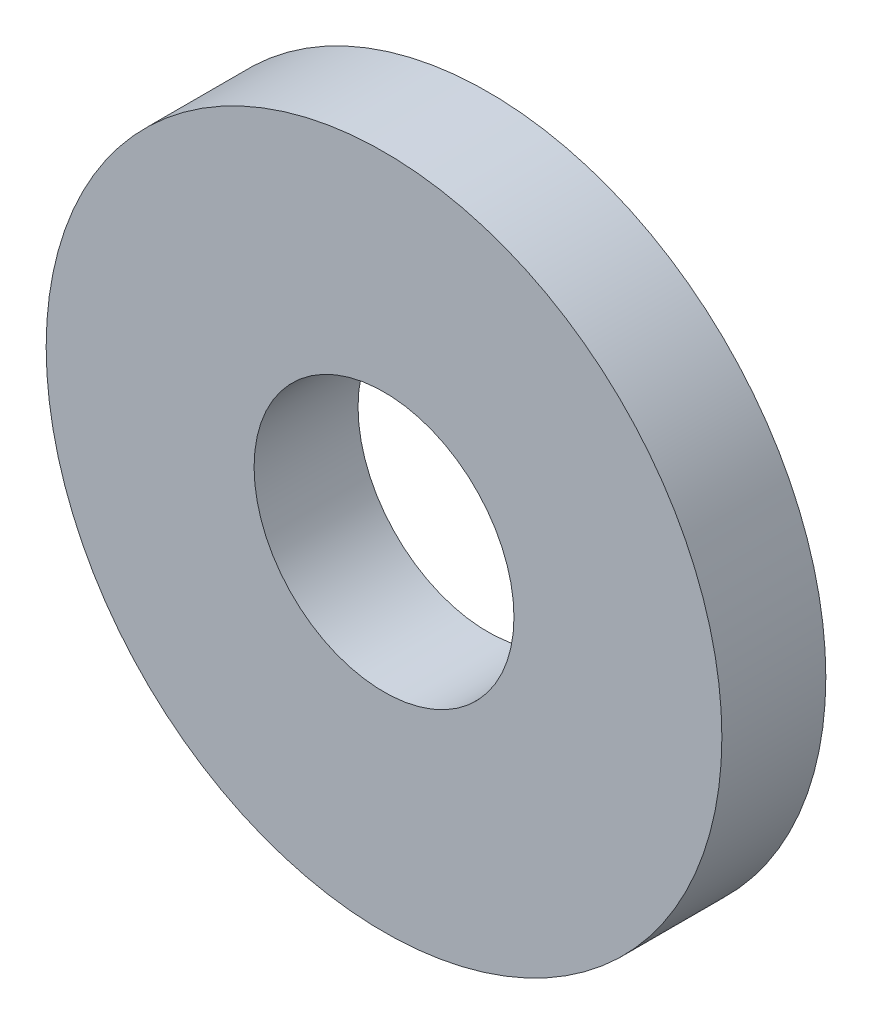
SolidWorks part; units mm, degrees
ref_plane "Front Plane" through (0, 0, 0) normal (0, 0, 1) x (1, 0, 0)
ref_plane "Top Plane" through (0, 0, 0) normal (0, 1, 0) x (1, 0, 0)
ref_plane "Right Plane" through (0, 0, 0) normal (1, 0, 0) x (0, 0, -1)
sketch "Sketch1" plane through (0, 0, 0) normal (0, 0, 1) x (1, 0, 0)
  circle A0 centre (0, 0) radius 2.5
  circle A1 centre (0, 0) radius 6.5
  dimension "D1" = 5
  dimension "D2" = 13
extrude "Boss-Extrude1" add sketch "Sketch1" along normal blind 2
